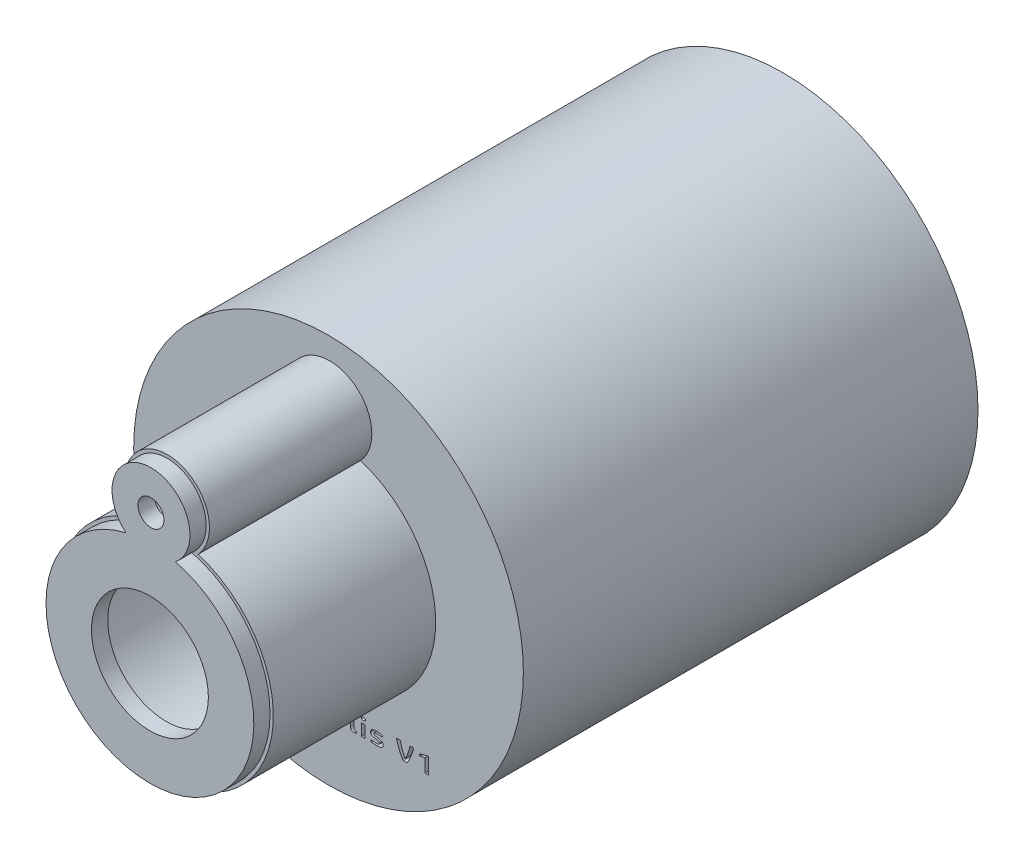
SolidWorks part; units mm, degrees
ref_plane "Front Plane" through (0, 0, 0) normal (0, 0, 1) x (1, 0, 0)
ref_plane "Top Plane" through (0, 0, 0) normal (0, 1, 0) x (1, 0, 0)
ref_plane "Right Plane" through (0, 0, 0) normal (1, 0, 0) x (0, 0, -1)
sketch "Sketch4" plane through (0, 0, 0) normal (0, 0, 1) x (1, 0, 0)
  circle A0 centre (0, 0) radius 60
  point P3 (0, 0)
extrude "Boss-Extrude1" add sketch "Sketch4" along normal blind 140 contours A0
sketch "Sketch5" plane through (0, 0, 140) normal (0, 0, 1) x (1, 0, 0)
  circle A1 centre (0.3308, 40.3616) radius 13
  circle A2 centre (0, 0) radius 33
extrude "Boss-Extrude2" add sketch "Sketch5" along normal blind 50 contours A1 A2
sketch "Sketch6" plane through (0, 0, 190) normal (0, 0, 1) x (1, 0, 0)
  circle A0 centre (0, 0) radius 28
  circle A1 centre (0.3308, 40.3616) radius 8
extrude "Cut-Extrude1" cut sketch "Sketch6" against normal blind 60
sketch "Sketch7" plane through (0, 0, 0) normal (0, 0, -1) x (-1, 0, 0)
  circle A0 centre (0, 0) radius 50
extrude "Cut-Extrude2" cut sketch "Sketch7" against normal blind 130
sketch "Sketch9" plane through (0, 0, 190) normal (0, 0, 1) x (1, 0, 0)
  circle A0 centre (0, 0) radius 32
  circle A1 centre (0.3308, 40.3616) radius 12
sketch "Sketch12" plane through (0, 0, 190) normal (0, 0, 1) x (1, 0, 0)
  circle A0 centre (0, 0) radius 32
extrude "Boss-Extrude4" add sketch "Sketch12" along normal blind 5
extrude "Boss-Extrude5" add sketch "Sketch9" along normal blind 5 contours A1
sketch "Sketch13" plane through (0, 0, 195) normal (0, 0, 1) x (1, 0, 0)
  circle A0 centre (0, 0) radius 18
extrude "Cut-Extrude5" cut sketch "Sketch13" against normal blind 5
sketch "Sketch14" plane through (0, 0, 195) normal (0, 0, 1) x (1, 0, 0)
  circle A0 centre (0.3308, 40.3616) radius 4
extrude "Cut-Extrude6" cut sketch "Sketch14" against normal blind 5
sketch "Sketch16" plane through (0, 0, 140) normal (0, 0, 1) x (1, 0, 0)
  text T0 "AquaPolis V1" font "@HP Simplified Hans" height in points 16
extrude "Cut-Extrude7" cut sketch "Sketch16" against normal blind 2
